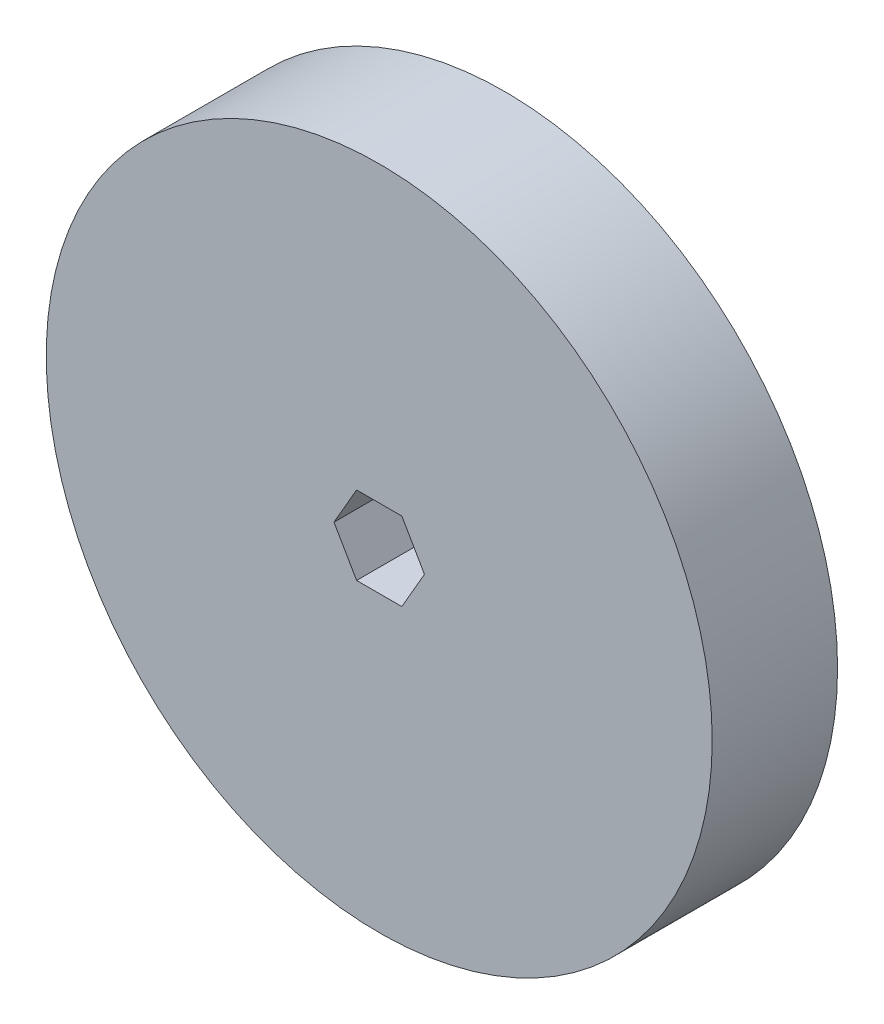
SolidWorks part; units mm, degrees
ref_plane "Front Plane" through (0, 0, 0) normal (0, 0, 1) x (1, 0, 0)
ref_plane "Top Plane" through (0, 0, 0) normal (0, 1, 0) x (1, 0, 0)
ref_plane "Right Plane" through (0, 0, 0) normal (1, 0, 0) x (0, 0, -1)
sketch "Sketch1" plane through (0, 0, 0) normal (0, 0, 1) x (1, 0, 0)
  line L1 (2.8868, 0) -> (1.4434, 2.5)
  line L2 (1.4434, 2.5) -> (-1.4434, 2.5)
  line L3 (-1.4434, 2.5) -> (-2.8868, 0)
  line L4 (-2.8868, 0) -> (-1.4434, -2.5)
  line L5 (-1.4434, -2.5) -> (1.4434, -2.5)
  line L6 (1.4434, -2.5) -> (2.8868, 0)
  circle A0 centre (0, 0) radius 21.25
  circle A1 centre (0, 0) radius 2.5 construction
extrude "Boss-Extrude1" add sketch "Sketch1" along normal blind 8
